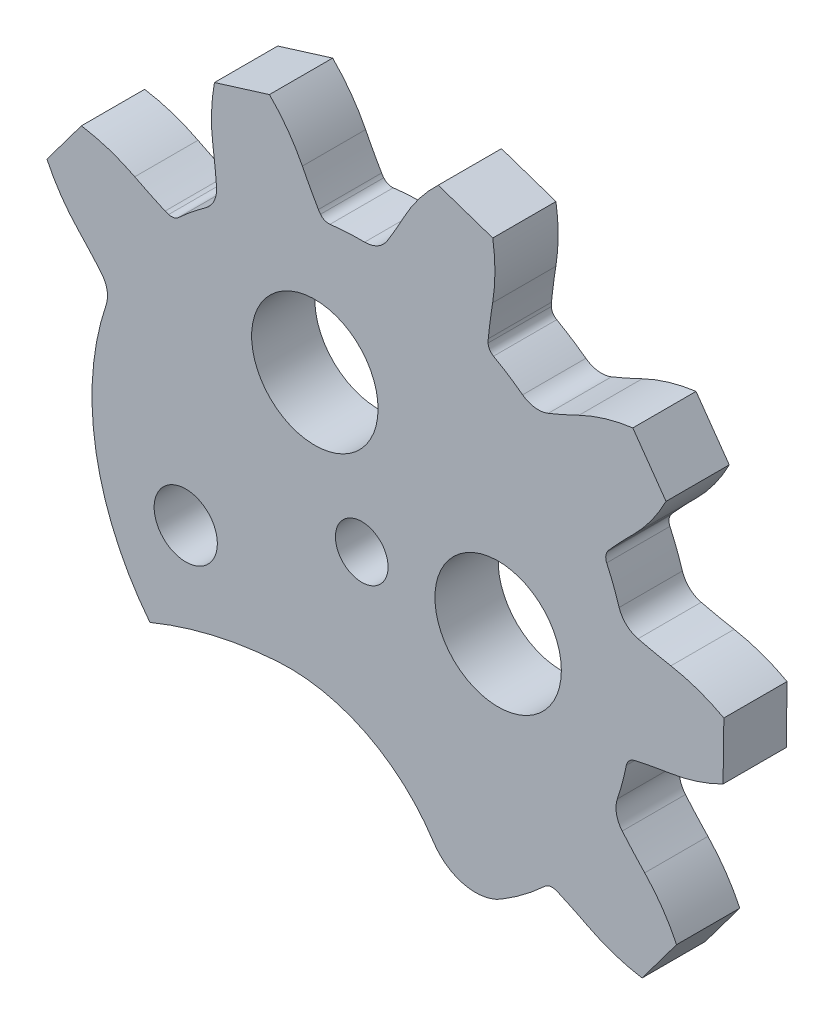
SolidWorks part; units mm, degrees
ref_plane "Plan de face" through (0, 0, 0) normal (0, 0, 1) x (1, 0, 0)
ref_plane "Plan de dessus" through (0, 0, 0) normal (0, 1, 0) x (1, 0, 0)
ref_plane "Plan de droite" through (0, 0, 0) normal (1, 0, 0) x (0, 0, -1)
sketch "Esquisse1" plane through (0, 0, 0) normal (0, 0, 1) x (1, 0, 0)
  line L0 (1028.9485, 2158.1621) -> (1057.1928, 2138.1765) construction
  line L1 (1028.9361, 2157.9296) -> (1057.3799, 2138.3317) construction
  line L2 (1036.1687, 2163.9267) -> (1038.778, 2164.7356)
  line L3 (1037.4733, 2164.3311) -> (1038.7681, 2160.1543) construction
  line L4 (1037.4733, 2164.3311) -> (1039.0291, 2160.2464) construction
  line L5 (1046.7882, 2165.0181) -> (1049.3746, 2164.1388)
  line L6 (1056.0211, 2159.6591) -> (1057.5967, 2157.4275)
  line L7 (1060.3407, 2149.8966) -> (1060.3037, 2147.1651)
  line L8 (1058.0971, 2139.4596) -> (1056.4616, 2137.2715)
  line L13 (1028.2188, 2156.8017) -> (1029.8543, 2158.9898)
  line L14 (1050.1473, 2132.3346) -> (1047.538, 2131.5257) [skipped]
  line L15 (1039.5278, 2131.2432) -> (1036.9414, 2132.1225) [skipped]
  line L16 (1030.2949, 2136.6022) -> (1028.7193, 2138.8338) [skipped]
  line L17 (1025.9752, 2146.3647) -> (1026.0123, 2149.0962) [skipped]
  circle A0 centre (1043.158, 2148.1307) radius 12.8 construction
  arc A1 (1036.1687, 2163.9267) -> (1036.1008, 2161.2626) centre (1044.4165, 2162.3836) ccw
  arc A2 (1036.1008, 2161.2626) -> (1036.2672, 2159.6762) centre (1009.2682, 2157.6455) cw
  arc A3 (1036.2672, 2159.6762) -> (1035.7459, 2158.5662) centre (1035.024, 2159.5827) cw
  arc A4 (1041.101, 2161.1747) -> (1041.2004, 2161.0285) centre (1042.1791, 2161.8008) ccw
  arc A5 (1040.3409, 2162.5771) -> (1041.101, 2161.1747) centre (1064.5142, 2174.7722) ccw
  arc A6 (1038.778, 2164.7356) -> (1040.3409, 2162.5771) centre (1032.8492, 2158.7977) cw
  arc A7 (1046.7882, 2165.0181) -> (1045.1674, 2162.9028) centre (1052.5539, 2158.9218) ccw
  arc A8 (1041.6517, 2160.8417) -> (1041.2004, 2161.0285) centre (1041.5929, 2161.3382) cw
  arc A9 (1045.1674, 2162.9028) -> (1044.3695, 2161.5215) centre (1021.3333, 2175.7483) cw
  arc A10 (1044.3695, 2161.5215) -> (1043.2954, 2160.9299) centre (1043.3088, 2162.1766) cw
  arc A11 (1049.3746, 2164.1388) -> (1049.3703, 2161.4739) centre (1041.0879, 2162.8198) cw
  arc A12 (1049.3703, 2161.4739) -> (1049.1609, 2159.8926) centre (1076.095, 2157.1312) ccw
  arc A13 (1049.1609, 2159.8926) -> (1049.1554, 2159.7159) centre (1050.4012, 2159.7654) ccw
  arc A14 (1049.4108, 2159.2995) -> (1049.1554, 2159.7159) centre (1049.655, 2159.7358) cw
  arc A15 (1056.0211, 2159.6591) -> (1053.4664, 2158.9005) centre (1057.1023, 2151.3381) ccw
  arc A16 (1053.4664, 2158.9005) -> (1052.0091, 2158.2519) centre (1041.7346, 2183.302) cw
  arc A17 (1052.0091, 2158.2519) -> (1050.7924, 2158.4047) centre (1051.536, 2159.4054) cw
  arc A18 (1057.5967, 2157.4275) -> (1056.0268, 2155.2741) centre (1050.1173, 2161.2312) cw
  arc A19 (1056.0268, 2155.2741) -> (1054.928, 2154.1178) centre (1075.095, 2136.0524) ccw
  arc A20 (1054.928, 2154.1178) -> (1054.8196, 2153.9781) centre (1055.8566, 2153.2859) ccw
  arc A21 (1054.7815, 2153.4911) -> (1054.8196, 2153.9781) centre (1055.2355, 2153.7005) cw
  arc A22 (1060.3407, 2149.8966) -> (1057.828, 2150.7844) centre (1056.3245, 2142.5293) ccw
  arc A23 (1057.828, 2150.7844) -> (1056.2678, 2151.1164) centre (1062.6797, 2177.4215) cw
  arc A24 (1056.2678, 2151.1164) -> (1055.3733, 2151.9552) centre (1056.5631, 2152.3277) cw
  arc A25 (1060.3037, 2147.1651) -> (1057.7679, 2146.3457) centre (1056.4885, 2154.6386) cw
  arc A26 (1057.7679, 2146.3457) -> (1056.1993, 2146.0562) centre (1061.8961, 2119.587) ccw
  arc A27 (1056.1993, 2146.0562) -> (1056.0295, 2146.0068) centre (1056.4616, 2144.8373) ccw
  arc A28 (1055.7124, 2145.6353) -> (1056.0295, 2146.0068) centre (1056.2028, 2145.5378) cw
  arc A29 (1058.0971, 2139.4596) -> (1056.5862, 2141.6548) centre (1050.5175, 2135.86) ccw
  arc A30 (1056.5862, 2141.6548) -> (1055.519, 2142.8404) centre (1076.1681, 2160.3529) cw
  arc A31 (1055.519, 2142.8404) -> (1055.2883, 2144.0448) centre (1056.4699, 2143.6468) cw
  arc A32 (1056.4616, 2137.2715) -> (1053.9285, 2138.0991) centre (1057.7679, 2145.5602) cw
  arc A33 (1053.9285, 2138.0991) -> (1052.4892, 2138.7869) centre (1041.5399, 2114.0243) ccw
  arc A34 (1052.4892, 2138.7869) -> (1052.3229, 2138.8467) centre (1051.985, 2137.6466) ccw
  arc A35 (1051.848, 2138.7325) -> (1052.3229, 2138.8467) centre (1052.1874, 2138.3654) cw
  arc A36 (1035.7459, 2158.5662) -> (1034.468, 2157.5288) centre (1043.158, 2148.1307) ccw
  arc A37 (1041.6517, 2160.8417) -> (1043.2954, 2160.9299) centre (1043.158, 2148.1306) cw
  arc A38 (1049.4108, 2159.2995) -> (1050.7924, 2158.4047) centre (1043.158, 2148.1307) cw
  arc A39 (1054.7815, 2153.4911) -> (1055.3733, 2151.9552) centre (1043.158, 2148.1307) cw
  arc A40 (1055.7124, 2145.6353) -> (1055.2883, 2144.0448) centre (1043.158, 2148.1307) cw
  arc A41 (1031.0276, 2152.2165) -> (1033.106, 2140.2061) centre (1043.158, 2148.1307) ccw
  arc A42 (1051.848, 2138.7325) -> (1051.8429, 2138.7279) centre (1043.155, 2148.1339) cw construction
  arc A43 (1033.106, 2140.2061) -> (1039.1388, 2141.6289) centre (1040.4705, 2122.4804) cw
  arc A44 (1039.1388, 2141.6289) -> (1046.5622, 2137.9152) centre (1039.7052, 2133.4849) cw
  arc A45 (1051.8429, 2138.7279) -> (1047.4485, 2136.0708) centre (1043.2842, 2147.9202) cw construction
  arc A46 (1049.783, 2137.1723) -> (1046.5622, 2137.9152) centre (1048.5552, 2139.2029) cw
  arc A47 (1047.4484, 2136.0711) -> (1047.4485, 2136.0708) centre (1039.7052, 2133.4849) cw
  arc A48 (1051.848, 2138.7325) -> (1049.783, 2137.1723) centre (1043.2835, 2147.9214) cw
  circle A49 centre (1043.158, 2148.1307) radius 1.25
  circle A50 centre (1040.9315, 2154.3956) radius 3
  circle A51 centre (1049.63, 2147.9944) radius 3
  circle A52 centre (1034.8062, 2145.0428) radius 1.5
  arc A64 (1028.2188, 2156.8017) -> (1029.7298, 2154.6065) centre (1035.7985, 2160.4013) ccw
  arc A65 (1029.7298, 2154.6065) -> (1030.7969, 2153.4209) centre (1010.1479, 2135.9084) cw
  arc A66 (1030.7969, 2153.4209) -> (1031.0276, 2152.2165) centre (1029.8461, 2152.6145) cw
  arc A67 (1029.8543, 2158.9898) -> (1032.3875, 2158.1622) centre (1028.5481, 2150.7011) cw
  arc A68 (1032.3875, 2158.1622) -> (1033.8267, 2157.4744) centre (1044.776, 2182.237) ccw
  arc A69 (1033.8267, 2157.4744) -> (1033.9931, 2157.4146) centre (1034.3309, 2158.6147) ccw
  arc A70 (1034.468, 2157.5288) -> (1033.9931, 2157.4146) centre (1034.1286, 2157.8959) cw
  arc A71 (1050.0487, 2136.5851) -> (1050.57, 2137.6951) centre (1051.292, 2136.6786) cw [skipped]
  arc A72 (1050.2152, 2134.9987) -> (1050.0487, 2136.5851) centre (1077.0478, 2138.6158) cw [skipped]
  arc A73 (1050.1473, 2132.3346) -> (1050.2152, 2134.9987) centre (1041.8994, 2133.8777) ccw [skipped]
  arc A74 (1047.538, 2131.5257) -> (1045.9751, 2133.6842) centre (1053.4667, 2137.4636) cw [skipped]
  arc A75 (1045.9751, 2133.6842) -> (1045.215, 2135.0866) centre (1021.8018, 2121.4891) ccw [skipped]
  arc A76 (1045.215, 2135.0866) -> (1045.1156, 2135.2328) centre (1044.1369, 2134.4605) ccw [skipped]
  arc A77 (1044.6643, 2135.4196) -> (1045.1156, 2135.2328) centre (1044.7231, 2134.9231) cw [skipped]
  arc A78 (1041.9464, 2134.7398) -> (1043.0206, 2135.3314) centre (1043.0072, 2134.0847) cw [skipped]
  arc A79 (1041.1486, 2133.3585) -> (1041.9464, 2134.7398) centre (1064.9827, 2120.513) cw [skipped]
  arc A80 (1039.5278, 2131.2432) -> (1041.1486, 2133.3585) centre (1033.7621, 2137.3395) ccw [skipped]
  arc A81 (1036.9414, 2132.1225) -> (1036.9457, 2134.7874) centre (1045.228, 2133.4415) cw [skipped]
  arc A82 (1036.9457, 2134.7874) -> (1037.155, 2136.3687) centre (1010.221, 2139.1301) ccw [skipped]
  arc A83 (1037.155, 2136.3687) -> (1037.1606, 2136.5454) centre (1035.9148, 2136.4959) ccw [skipped]
  arc A84 (1036.9052, 2136.9618) -> (1037.1606, 2136.5454) centre (1036.661, 2136.5255) cw [skipped]
  arc A85 (1034.3069, 2138.0094) -> (1035.5236, 2137.8566) centre (1034.78, 2136.8559) cw [skipped]
  arc A86 (1032.8495, 2137.3608) -> (1034.3069, 2138.0094) centre (1044.5813, 2112.9593) cw [skipped]
  arc A87 (1030.2949, 2136.6022) -> (1032.8495, 2137.3608) centre (1029.2137, 2144.9232) ccw [skipped]
  arc A88 (1028.7193, 2138.8338) -> (1030.2891, 2140.9872) centre (1036.1986, 2135.0301) cw [skipped]
  arc A89 (1030.2891, 2140.9872) -> (1031.388, 2142.1435) centre (1011.221, 2160.209) ccw [skipped]
  arc A90 (1031.388, 2142.1435) -> (1031.4963, 2142.2832) centre (1030.4594, 2142.9754) ccw [skipped]
  arc A91 (1031.5345, 2142.7702) -> (1031.4963, 2142.2832) centre (1031.0805, 2142.5608) cw [skipped]
  arc A92 (1030.0482, 2145.1449) -> (1030.9427, 2144.3061) centre (1029.7529, 2143.9336) cw [skipped]
  arc A93 (1028.4879, 2145.4769) -> (1030.0482, 2145.1449) centre (1023.6363, 2118.8398) cw [skipped]
  arc A94 (1025.9752, 2146.3647) -> (1028.4879, 2145.4769) centre (1029.9915, 2153.732) ccw [skipped]
  arc A95 (1026.0123, 2149.0962) -> (1028.5481, 2149.9156) centre (1029.8275, 2141.6227) cw [skipped]
  arc A96 (1028.5481, 2149.9156) -> (1030.1167, 2150.2051) centre (1024.4198, 2176.6743) ccw [skipped]
  arc A97 (1030.1167, 2150.2051) -> (1030.2865, 2150.2545) centre (1029.8544, 2151.424) ccw [skipped]
  arc A98 (1030.6036, 2150.626) -> (1030.2865, 2150.2545) centre (1030.1132, 2150.7235) cw [skipped]
  point P7 (1043.158, 2148.1307)
  point P28 (1041.3783, 2160.8063)
  point P173 (1043.158, 2148.1307)
  dimension "D2" = 25.6
  dimension "D3" = 0.5
  dimension "D5" = 2.5
  dimension "D6" = 6
  dimension "D7" = 3
  dimension "D8" = 4.8
  dimension "D1" = 34.6
  dimension "D4" = 10
extrude "Boss.-Extru.1" add sketch "Esquisse1" along normal blind 3 contours A36 A70 A69 A68 A67 L13 A64 A65 A66 A41 A43 A44 A46 A48 A35 A34 A33 A32 L8 A29 A30 A31 A40 A28 A27 A26 A25 L7 A22 A23 A24 A39 A21 A20 A19 A18 L6 A15 A16 A17 A38 A14 A13 A12 A11 L5 A7 A9 A10 A37 A8
